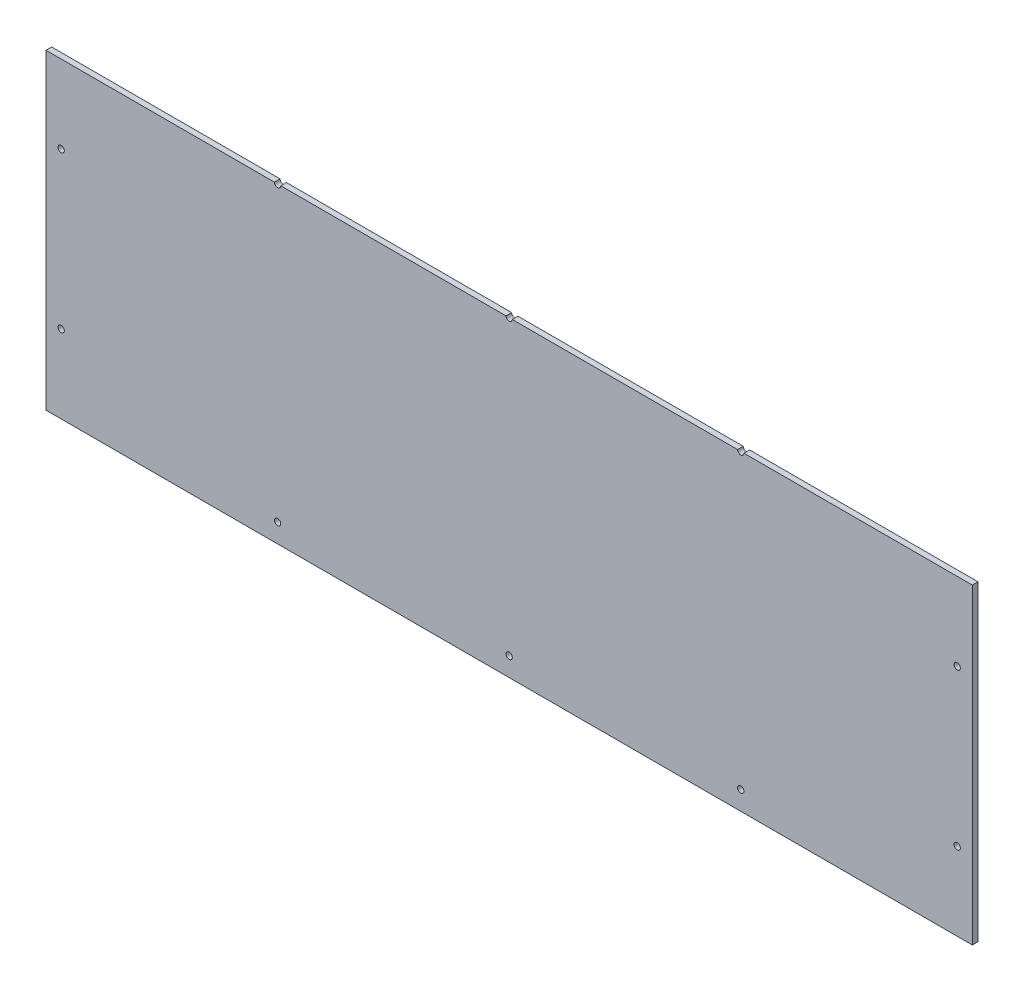
SolidWorks part; units mm, degrees
ref_plane "Front Plane" through (0, 0, 0) normal (0, 0, 1) x (1, 0, 0)
ref_plane "Top Plane" through (0, 0, 0) normal (0, 1, 0) x (1, 0, 0)
ref_plane "Right Plane" through (0, 0, 0) normal (1, 0, 0) x (0, 0, -1)
sketch "Sketch1" plane through (0, 0, 0) normal (0, 0, 1) x (1, 0, 0)
  line L1 (-367, 123.5) -> (-186, 123.5)
  line L2 (-367, 123.5) -> (-367, -123.5)
  line L4 (367, 123.5) -> (367, -123.5)
  line L10 (-367, -123.5) -> (367, -123.5)
  line L11 (0, -123.5) -> (0, 123.5) construction
  line L12 (-181, 123.5) -> (-2.5, 123.5)
  line L13 (2.5, 123.5) -> (181, 123.5)
  line L14 (186, 123.5) -> (367, 123.5)
  line L16 (-367, 0) -> (367, 0) construction
  arc A3 (-2.5, 123.5) -> (2.5, 123.5) centre (0, 123.5) ccw
  arc A4 (181, 123.5) -> (186, 123.5) centre (183.5, 123.5) ccw
  arc A5 (-186, 123.5) -> (-181, 123.5) centre (-183.5, 123.5) ccw
  circle A8 centre (-355, 61.75) radius 2.5
  circle A9 centre (-355, -61.75) radius 2.5
  circle A10 centre (355, -61.75) radius 2.5
  circle A12 centre (355, 61.75) radius 2.5
  circle A14 centre (-183.5, -108.5) radius 2.5
  circle A15 centre (0, -108.5) radius 2.5
  circle A16 centre (183.5, -108.5) radius 2.5
  point P18 (-367, 123.5)
  dimension "D5" = 2
  dimension "D3" = 5
  dimension "D7" = 12
  dimension "D10" = 15
  dimension "D11" = 183.5
  dimension "D1" = 247
  dimension "D2" = 734
  dimension "D4" = 367
  dimension "D8" = 12
  dimension "D6" = 2
  dimension "D12" = 3
extrude "Boss-Extrude1" add sketch "Sketch1" along normal blind 4.5
